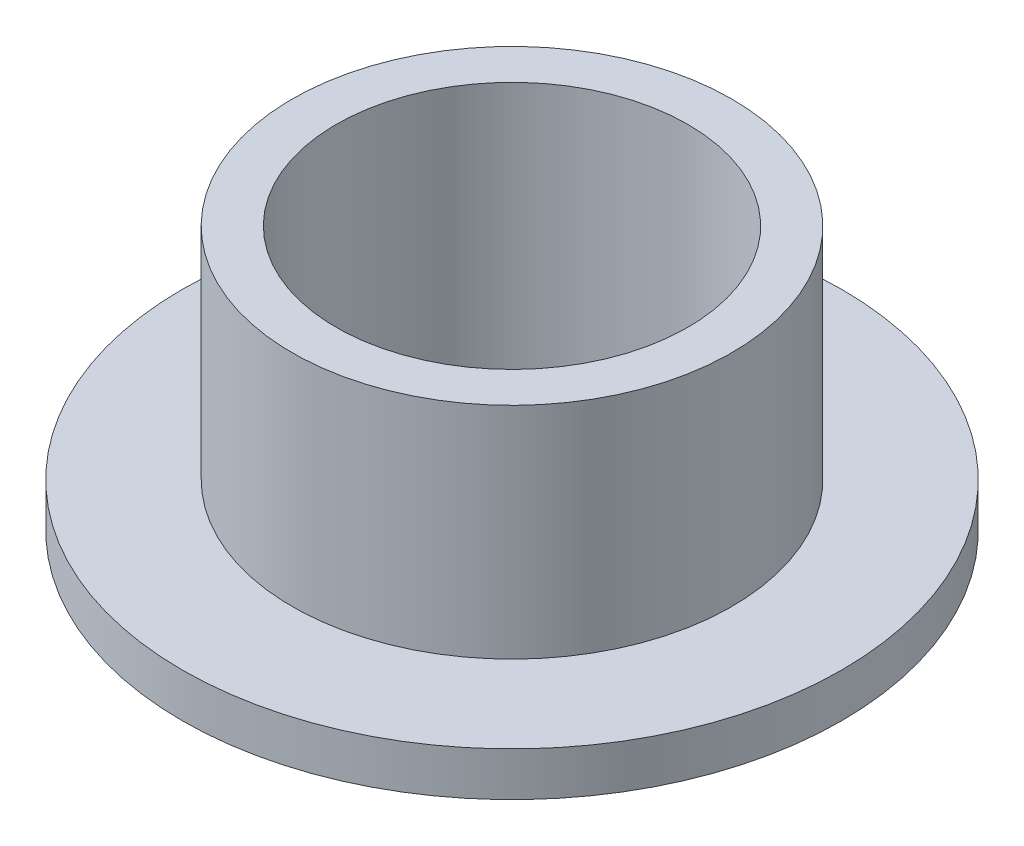
SolidWorks part; units mm, degrees
material "acero"
ref_plane "Alzado" through (0, 0, 0) normal (0, 0, 1) x (1, 0, 0)
ref_plane "Planta" through (0, 0, 0) normal (0, 1, 0) x (1, 0, 0)
ref_plane "Vista lateral" through (0, 0, 0) normal (1, 0, 0) x (0, 0, -1)
sketch "Croquis1" plane through (0, 0, 0) normal (0, 0, 1) x (1, 0, 0)
  line L0 (0, 0) -> (0, 57.7811) construction
  line L1 (-4, 6) -> (-4, 0)
  line L2 (-4, 0) -> (-7.5, 0)
  line L3 (-7.5, 0) -> (-7.5, 1)
  line L4 (-7.5, 1) -> (-5, 1)
  line L5 (-5, 1) -> (-5, 6)
  line L6 (-5, 6) -> (-4, 6)
  dimension "D1" = 8
  dimension "D2" = 10
  dimension "D3" = 1
  dimension "D4" = 15
  dimension "D5" = 6
revolve "Revolución1" add sketch "Croquis1" angle 360 about L0
